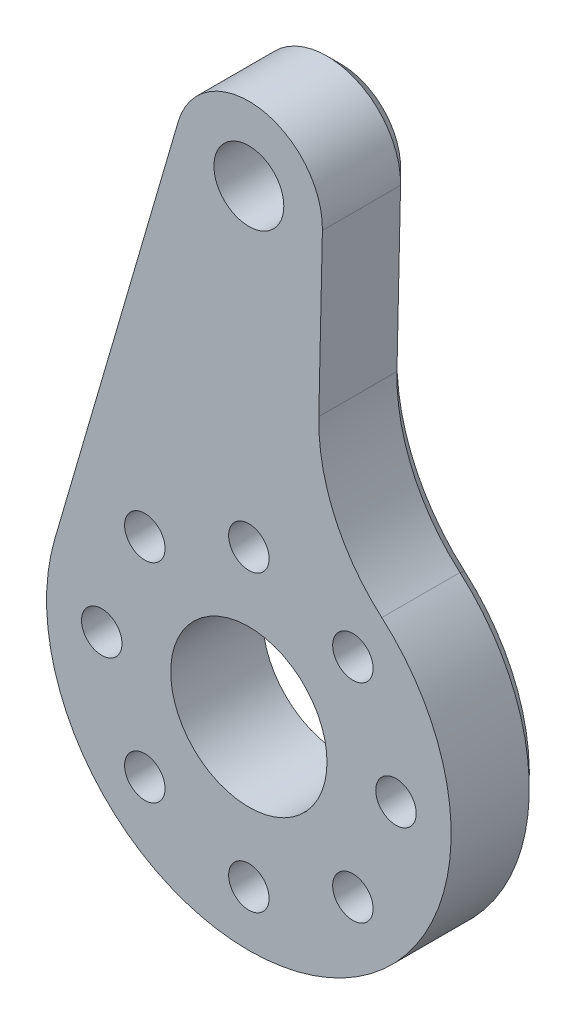
SolidWorks part; units mm, degrees
ref_plane "Front Plane" through (0, 0, 0) normal (0, 0, 1) x (1, 0, 0)
ref_plane "Top Plane" through (0, 0, 0) normal (0, 1, 0) x (1, 0, 0)
ref_plane "Right Plane" through (0, 0, 0) normal (1, 0, 0) x (0, 0, -1)
sketch "Sketch1" plane through (0, 0, 0) normal (0, 0, 1) x (1, 0, 0)
  line L0 (-18.5581, 4.6161) -> (-25.2781, -18.4239)
  line L3 (-10.8781, 4.6161) -> (-4.1581, -18.4239)
  line L4 (-14.7181, 0.8298) -> (-14.7181, 20.8298) construction
  line L5 (-14.3669, -21.5039) -> (49985.6331, -21.5039) construction
  circle A2 centre (-14.7181, 3.4961) radius 1.9
  circle A3 centre (-14.7181, -21.5039) radius 4.25
  arc A5 (-10.8781, 4.6161) -> (-18.5581, 4.6161) centre (-14.7181, 3.4961) ccw
  arc A6 (-25.2781, -18.4239) -> (-4.1581, -18.4239) centre (-14.7181, -21.5039) ccw
  circle A7 centre (-15.0314, -20.0888) radius 11 construction
  circle A8 centre (-6.7181, -21.5039) radius 1.1
  circle A9 centre (-9.0613, -27.1608) radius 1.1
  circle A10 centre (-14.7181, -29.5039) radius 1.1
  circle A11 centre (-20.375, -27.1608) radius 1.1
  circle A12 centre (-22.7181, -21.5039) radius 1.1
  circle A13 centre (-20.375, -15.847) radius 1.1
  circle A14 centre (-14.7181, -13.5039) radius 1.1
  circle A15 centre (-9.0613, -15.847) radius 1.1
  point P30 (-14.7181, -21.5039)
  dimension "D1" = 3.8
  dimension "D3" = 25
  dimension "D4" = 11
  dimension "D2" = 4
  dimension "D5" = 8.5
  dimension "D6" = 2.2
  dimension "D7" = 8
  dimension "D8" = 8
extrude "Boss-Extrude1" add sketch "Sketch1" along normal blind 5
sketch "Sketch2" plane through (0, 0, 5) normal (0, 0, 1) x (1, 0, 0)
  circle A0 centre (-14.7181, -21.5039) radius 11.5
  dimension "D1" = 23
extrude "Cut-Extrude1" [suppressed] cut sketch "Sketch2" against normal blind 1.75
sketch "Sketch5" plane through (0, 0, 5) normal (0, 0, 1) x (1, 0, 0)
  circle A2 centre (-14.8897, 3.8764) radius 1.55
  circle A3 centre (-14.8897, 3.8764) radius 8
extrude "Boss-Extrude2" [suppressed] add sketch "Sketch5" along normal blind 3
fillet "Fillet1" [suppressed] radius 1
sketch "Sketch4" plane through (0, 0, 0) normal (0, 0, -1) x (-1, 0, 0)
  circle A0 centre (22.7181, -21.5039) radius 1.75
  circle A1 centre (20.375, -27.1608) radius 1.75
  circle A2 centre (14.7181, -29.5039) radius 1.75
  circle A3 centre (9.0613, -27.1608) radius 1.75
  circle A4 centre (6.7181, -21.5039) radius 1.75
  circle A5 centre (9.0613, -15.847) radius 1.75
  circle A6 centre (14.7181, -13.5039) radius 1.75
  circle A7 centre (20.375, -15.847) radius 1.75
  circle A10 centre (14.7181, -21.5039) radius 4.25 construction
  point P20 (14.7181, -21.5039)
  dimension "D1" = 3.5
extrude "Cut-Extrude3" cut sketch "Sketch4" against normal blind 2.25
sketch "Croquis1" plane through (0, 0, 0) normal (0, 0, -1) x (-1, 0, 0)
  line L0 (10.7191, 3.4081) -> (11.0391, -11.1374)
  line L1 (18.5581, 4.6161) -> (25.2781, -18.4239) construction
  line L2 (10.8781, 4.6161) -> (4.1581, -18.4239)
  arc A0 (10.8781, 4.6161) -> (10.7191, 3.4081) centre (14.7181, 3.4961) ccw
  arc A1 (4.1581, -18.4239) -> (11.0391, -11.1374) centre (14.7181, -21.5039) cw
  dimension "D1" = 15
extrude "Cortar-Extruir1" cut sketch "Croquis1" against normal blind 10
fillet "Redondeo1" radius 10 1 edges at (-11.0391, -11.1374, 2.5)
chamfer "Chaflán1" distance 0.75 angle 45 5 edges at (-21.9181, -6.9039, 0) (-11.626, -32.0604, 0) (-14.1089, 7.4494, 0) (-10.8166, -1.0241, 0) (-10.0643, -9.7158, 0)
